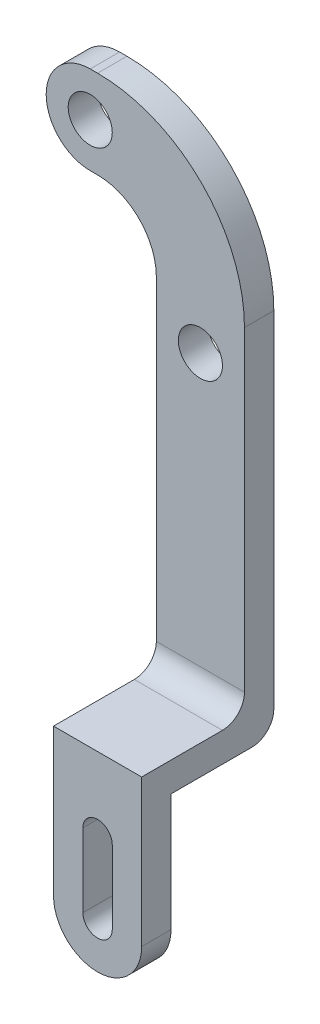
SolidWorks part; units mm, degrees
ref_plane "Front" through (0, 0, 0) normal (0, 0, 1) x (1, 0, 0)
ref_plane "Top" through (0, 0, 0) normal (0, 1, 0) x (1, 0, 0)
ref_plane "Right" through (0, 0, 0) normal (1, 0, 0) x (0, 0, -1)
sketch "Sketch1" plane through (0, 0, 0) normal (0, 0, 1) x (1, 0, 0)
  line L0 (-90.6722, 18.5996) -> (-90.6722, 68.5996) construction
  line L1 (-96.6722, 8.5996) -> (-96.6722, 74.5996)
  line L2 (-84.6722, 8.5996) -> (-84.6722, 74.5996)
  line L3 (-90.6722, 8.5996) -> (-90.6722, 18.5996) construction
  line L4 (-92.6722, 8.5996) -> (-92.6722, 18.5996)
  line L5 (-88.6722, 8.5996) -> (-88.6722, 18.5996)
  line L6 (-105.6722, 94.5996) -> (-104.6722, 94.5996)
  line L7 (-105.6722, 82.5996) -> (-104.6722, 82.5996)
  arc A0 (-96.6722, 8.5996) -> (-84.6722, 8.5996) centre (-90.6722, 8.5996) ccw
  arc A1 (-105.6722, 94.5996) -> (-105.6722, 82.5996) centre (-105.6722, 88.5996) ccw
  arc A2 (-92.6722, 8.5996) -> (-88.6722, 8.5996) centre (-90.6722, 8.5996) ccw
  arc A3 (-88.6722, 18.5996) -> (-92.6722, 18.5996) centre (-90.6722, 18.5996) ccw
  circle A4 centre (-90.6722, 68.5996) radius 3
  arc A5 (-84.6722, 74.5996) -> (-104.6722, 94.5996) centre (-104.6722, 74.5996) ccw
  circle A6 centre (-105.6722, 88.5996) radius 3
  arc A7 (-96.6722, 74.5996) -> (-104.6722, 82.5996) centre (-104.6722, 74.5996) ccw
  point P9 (-90.6722, 13.5996)
  dimension "D1" = 6
  dimension "D2" = 10
  dimension "D3" = 15
  dimension "D4" = 2
  dimension "D5" = 55
  dimension "D6" = 12
  dimension "D7" = 6
  dimension "D8" = 20
  dimension "D9" = 20
  dimension "D10" = 8
  dimension "D11" = 50
extrude "Boss-Extrude1" add sketch "Sketch1" along normal blind 4
sketch "Sketch2" plane through (0, 0, 4) normal (0, 0, -1) x (-1, 0, 0)
  line L0 (84.6722, 28.5996) -> (96.6722, 28.5996)
  line L1 (84.6722, 8.5996) -> (84.6722, 74.5996) construction
  line L2 (96.6722, 74.5996) -> (96.6722, 8.5996) construction
  line L3 (96.6722, 28.5996) -> (96.6722, 8.5996)
  line L4 (84.6722, 8.5996) -> (84.6722, 28.5996)
  line L5 (88.6722, 8.5996) -> (88.6722, 18.5996) construction
  line L6 (92.6722, 18.5996) -> (92.6722, 8.5996) construction
  line L7 (88.6722, 8.5996) -> (88.6722, 18.5996)
  line L8 (92.6722, 18.5996) -> (92.6722, 8.5996)
  arc A0 (84.6722, 8.5996) -> (96.6722, 8.5996) centre (90.6722, 8.5996) ccw construction
  arc A1 (84.6722, 8.5996) -> (96.6722, 8.5996) centre (90.6722, 8.5996) ccw
  arc A2 (92.6722, 18.5996) -> (88.6722, 18.5996) centre (90.6722, 18.5996) ccw construction
  arc A3 (88.6722, 8.5996) -> (92.6722, 8.5996) centre (90.6722, 8.5996) ccw construction
  arc A4 (88.6722, 8.5996) -> (92.6722, 8.5996) centre (90.6722, 8.5996) ccw
  arc A7 (92.6722, 18.5996) -> (88.6722, 18.5996) centre (90.6722, 18.5996) ccw construction
  arc A8 (92.6722, 18.5996) -> (88.6722, 18.5996) centre (90.6722, 18.5996) ccw
  dimension "D1" = 10
extrude "Boss-Extrude2" add sketch "Sketch2" against normal blind 14
sketch "Sketch3" plane through (0, 0, 0) normal (0, 0, -1) x (-1, 0, 0)
  line L0 (88.6722, 8.5996) -> (88.6722, 18.5996) construction
  line L1 (92.6722, 18.5996) -> (92.6722, 8.5996) construction
  line L2 (84.6722, 8.5996) -> (84.6722, 74.5996) construction
  line L3 (96.6722, 74.5996) -> (96.6722, 8.5996) construction
  line L4 (88.6722, 8.5996) -> (88.6722, 18.5996)
  line L5 (92.6722, 18.5996) -> (92.6722, 8.5996)
  line L6 (84.6722, 8.5996) -> (84.6722, 24.5996)
  line L7 (96.6722, 24.5996) -> (96.6722, 8.5996)
  line L8 (84.6722, 24.5996) -> (96.6722, 24.5996)
  line L9 (96.6722, 28.5996) -> (84.6722, 28.5996) construction
  arc A0 (88.6722, 8.5996) -> (92.6722, 8.5996) centre (90.6722, 8.5996) ccw construction
  arc A1 (92.6722, 18.5996) -> (88.6722, 18.5996) centre (90.6722, 18.5996) ccw construction
  arc A2 (84.6722, 8.5996) -> (96.6722, 8.5996) centre (90.6722, 8.5996) ccw construction
  arc A3 (88.6722, 8.5996) -> (92.6722, 8.5996) centre (90.6722, 8.5996) ccw
  arc A4 (92.6722, 18.5996) -> (88.6722, 18.5996) centre (90.6722, 18.5996) ccw
  arc A5 (84.6722, 8.5996) -> (96.6722, 8.5996) centre (90.6722, 8.5996) ccw
  dimension "D1" = 6
  dimension "D2" = 4
extrude "Cut-Extrude1" cut sketch "Sketch3" against normal blind 14
fillet "Fillet1" radius 3 2 edges at (-90.6722, 24.5996, 0)
